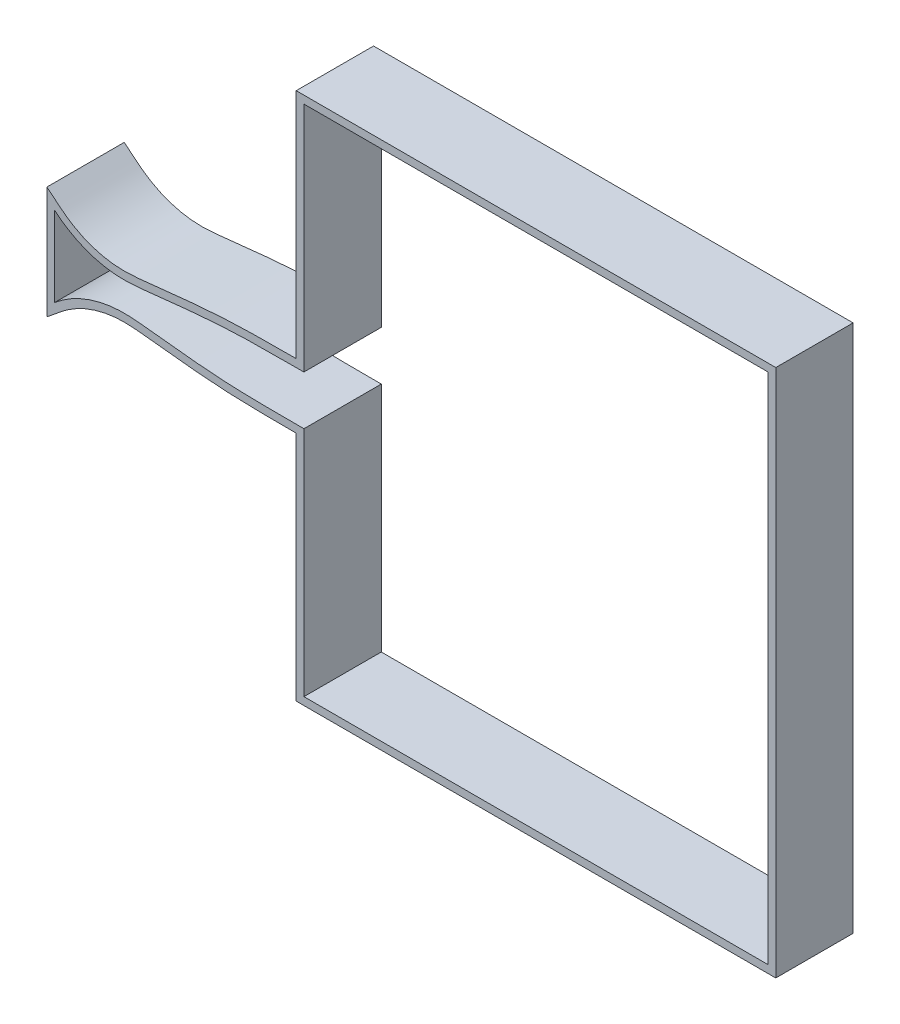
SolidWorks part; units mm, degrees
ref_plane "Front Plane"
ref_plane "Top Plane" through (0, 0, 0) normal (0, 1, 0) x (1, 0, 0)
ref_plane "Right Plane" through (0, 0, 0) normal (1, 0, 0) x (0, 0, -1)
curve "Curve1"
  spline degree 3 poles (-8.9943, 5.1625, 0) (-8.9922, 5.1608, 0) (-8.9859, 5.1556, 0) (-8.9711, 5.1434, 0) (-8.9416, 5.1188, 0) (-8.8898, 5.0757, 0) (-8.8197, 5.0179, 0) (-8.7395, 4.9527, 0) (-8.6589, 4.888, 0) (-8.5778, 4.824, 0) (-8.4963, 4.7605, 0) (-8.4142, 4.6976, 0) (-8.3317, 4.6353, 0) (-8.2488, 4.5736, 0) (-8.1654, 4.5124, 0) (-8.0816, 4.452, 0) (-7.9974, 4.3921, 0) (-7.9126, 4.3328, 0) (-7.8275, 4.2742, 0) (-7.742, 4.2163, 0) (-7.656, 4.1589, 0) (-7.5696, 4.1023, 0) (-7.4828, 4.0462, 0) (-7.3957, 3.9908, 0) (-7.3081, 3.9361, 0) (-7.2201, 3.882, 0) (-7.1317, 3.8286, 0) (-7.0429, 3.7759, 0) (-6.9538, 3.7238, 0) (-6.8643, 3.6723, 0) (-6.7744, 3.6216, 0) (-6.6841, 3.5715, 0) (-6.5935, 3.5221, 0) (-6.5025, 3.4734, 0) (-6.4112, 3.4253, 0) (-6.3195, 3.378, 0) (-6.2275, 3.3313, 0) (-6.1352, 3.2854, 0) (-6.0425, 3.24, 0) (-5.9495, 3.1954, 0) (-5.8562, 3.1515, 0) (-5.7625, 3.1084, 0) (-5.6686, 3.0658, 0) (-5.5744, 3.024, 0) (-5.4798, 2.9829, 0) (-5.385, 2.9425, 0) (-5.2898, 2.9028, 0) (-5.1944, 2.8639, 0) (-5.0987, 2.8256, 0) (-5.0028, 2.7881, 0) (-4.9065, 2.7512, 0) (-4.81, 2.7151, 0) (-4.7133, 2.6797, 0) (-4.6162, 2.6451, 0) (-4.519, 2.6111, 0) (-4.4215, 2.5779, 0) (-4.3237, 2.5454, 0) (-4.2258, 2.5137, 0) (-4.1276, 2.4826, 0) (-4.0292, 2.4524, 0) (-3.9306, 2.4227, 0) (-3.8317, 2.394, 0) (-3.7327, 2.3659, 0) (-3.6334, 2.3385, 0) (-3.534, 2.3119, 0) (-3.4344, 2.2861, 0) (-3.3346, 2.2609, 0) (-3.2346, 2.2365, 0) (-3.1344, 2.2129, 0) (-3.0341, 2.19, 0) (-2.9336, 2.1679, 0) (-2.833, 2.1465, 0) (-2.7322, 2.1258, 0) (-2.6313, 2.106, 0) (-2.5302, 2.0868, 0) (-2.4291, 2.0684, 0) (-2.3277, 2.0508, 0) (-2.2263, 2.0339, 0) (-2.1247, 2.0178, 0) (-2.0231, 2.0024, 0) (-1.9213, 1.9878, 0) (-1.8194, 1.974, 0) (-1.7175, 1.9609, 0) (-1.6154, 1.9486, 0) (-1.5133, 1.937, 0) (-1.411, 1.9262, 0) (-1.3088, 1.9161, 0) (-1.2064, 1.9068, 0) (-1.104, 1.8983, 0) (-1.0015, 1.8906, 0) (-0.899, 1.8836, 0) (-0.7965, 1.8773, 0) (-0.6939, 1.8719, 0) (-0.5913, 1.8672, 0) (-0.4886, 1.8632, 0) (-0.3859, 1.8601, 0) (-0.2832, 1.8576, 0) (-0.1805, 1.856, 0) (-0.0778, 1.8551, 0) (0.0249, 1.8549, 0) (0.1276, 1.8557, 0) (0.2302, 1.8571, 0) (0.3329, 1.8592, 0) (0.4355, 1.8621, 0) (0.5381, 1.8656, 0) (0.6407, 1.87, 0) (0.7433, 1.8748, 0) (0.8458, 1.8804, 0) (0.9483, 1.8864, 0) (1.0508, 1.893, 0) (1.1532, 1.9, 0) (1.2556, 1.9073, 0) (1.358, 1.9151, 0) (1.4604, 1.9232, 0) (1.5627, 1.9316, 0) (1.6651, 1.9402, 0) (1.7673, 1.9492, 0) (1.8696, 1.9583, 0) (1.9719, 1.9677, 0) (2.0742, 1.9772, 0) (2.1764, 1.9869, 0) (2.2786, 1.9969, 0) (2.3808, 2.0068, 0) (2.483, 2.017, 0) (2.5852, 2.0272, 0) (2.6874, 2.0375, 0) (2.7896, 2.048, 0) (2.8918, 2.0585, 0) (2.9939, 2.0691, 0) (3.0961, 2.0797, 0) (3.1982, 2.0904, 0) (3.3004, 2.1012, 0) (3.4025, 2.112, 0) (3.5047, 2.1228, 0) (3.6068, 2.1336, 0) (3.709, 2.1445, 0) (3.8111, 2.1554, 0) (3.9132, 2.1663, 0) (4.0154, 2.1772, 0) (4.1175, 2.1882, 0) (4.2196, 2.1991, 0) (4.3218, 2.21, 0) (4.4239, 2.221, 0) (4.526, 2.2319, 0) (4.6282, 2.2428, 0) (4.7303, 2.2538, 0) (4.8324, 2.2647, 0) (4.9346, 2.2757, 0) (5.0367, 2.2866, 0) (5.1388, 2.2976, 0) (5.241, 2.3085, 0) (5.3431, 2.3195, 0) (5.4453, 2.3304, 0) (5.5474, 2.3414, 0) (5.6495, 2.3523, 0) (5.7517, 2.3633, 0) (5.8538, 2.3742, 0) (5.9559, 2.3852, 0) (6.0581, 2.3962, 0) (6.1602, 2.4071, 0) (6.2623, 2.4181, 0) (6.3645, 2.4291, 0) (6.4666, 2.4401, 0) (6.5687, 2.451, 0) (6.6709, 2.462, 0) (6.773, 2.4729, 0) (6.8752, 2.4838, 0) (6.9773, 2.4947, 0) (7.0795, 2.5056, 0) (7.1816, 2.5165, 0) (7.2837, 2.5273, 0) (7.3859, 2.5382, 0) (7.4881, 2.5489, 0) (7.5902, 2.5596, 0) (7.6924, 2.5704, 0) (7.7946, 2.581, 0) (7.8967, 2.5916, 0) (7.9989, 2.6021, 0) (8.1011, 2.6126, 0) (8.2033, 2.623, 0) (8.3055, 2.6334, 0) (8.4077, 2.6436, 0) (8.5099, 2.6539, 0) (8.6122, 2.664, 0) (8.7144, 2.6741, 0) (8.8166, 2.684, 0) (8.9189, 2.6939, 0) (9.0211, 2.7037, 0) (9.1234, 2.7134, 0) (9.2257, 2.723, 0) (9.3279, 2.7325, 0) (9.4302, 2.742, 0) (9.5325, 2.7513, 0) (9.6348, 2.7605, 0) (9.7371, 2.7697, 0) (9.8395, 2.7786, 0) (9.9418, 2.7876, 0) (10.0442, 2.7963, 0) (10.1465, 2.8051, 0) (10.2489, 2.8136, 0) (10.3512, 2.8221, 0) (10.4536, 2.8304, 0) (10.556, 2.8387, 0) (10.6584, 2.8468, 0) (10.7608, 2.8549, 0) (10.8632, 2.8627, 0) (10.9657, 2.8705, 0) (11.0681, 2.8782, 0) (11.1705, 2.8857, 0) (11.273, 2.8932, 0) (11.3754, 2.9005, 0) (11.4779, 2.9078, 0) (11.5804, 2.9148, 0) (11.6828, 2.9218, 0) (11.7853, 2.9287, 0) (11.8878, 2.9355, 0) (11.9903, 2.942, 0) (12.0928, 2.9486, 0) (12.1953, 2.9549, 0) (12.2979, 2.9613, 0) (12.4004, 2.9675, 0) (12.5029, 2.9735, 0) (12.6055, 2.9795, 0) (12.708, 2.9853, 0) (12.8106, 2.9911, 0) (12.9131, 2.9967, 0) (13.0157, 3.0022, 0) (13.1183, 3.0076, 0) (13.2208, 3.0129, 0) (13.3234, 3.0182, 0) (13.426, 3.0232, 0) (13.5286, 3.0282, 0) (13.6312, 3.0331, 0) (13.7338, 3.0378, 0) (13.8364, 3.0425, 0) (13.939, 3.0471, 0) (14.0416, 3.0515, 0) (14.1442, 3.0559, 0) (14.2468, 3.0601, 0) (14.3495, 3.0642, 0) (14.4521, 3.0683, 0) (14.5547, 3.0722, 0) (14.6574, 3.0761, 0) (14.76, 3.0798, 0) (14.8626, 3.0835, 0) (14.9653, 3.087, 0) (15.0679, 3.0904, 0) (15.1706, 3.0938, 0) (15.2732, 3.097, 0) (15.3759, 3.1002, 0) (15.4786, 3.1032, 0) (15.5812, 3.1062, 0) (15.6839, 3.109, 0) (15.7866, 3.1118, 0) (15.8892, 3.1146, 0) (15.9919, 3.1171, 0) (16.0946, 3.1197, 0) (16.1972, 3.1221, 0) (16.2999, 3.1244, 0) (16.4026, 3.1267, 0) (16.5053, 3.1289, 0) (16.608, 3.131, 0) (16.7106, 3.133, 0) (16.8133, 3.1349, 0) (16.916, 3.1368, 0) (17.0187, 3.1386, 0) (17.1214, 3.1403, 0) (17.2241, 3.142, 0) (17.3268, 3.1436, 0) (17.4295, 3.1451, 0) (17.5321, 3.1465, 0) (17.6348, 3.1479, 0) (17.7375, 3.1492, 0) (17.8402, 3.1505, 0) (17.9429, 3.1517, 0) (18.0456, 3.1529, 0) (18.1483, 3.154, 0) (18.251, 3.1551, 0) (18.3537, 3.156, 0) (18.4564, 3.157, 0) (18.5591, 3.1579, 0) (18.6618, 3.1587, 0) (18.7645, 3.1596, 0) (18.8672, 3.1604, 0) (18.9699, 3.161, 0) (19.0726, 3.1617, 0) (19.1752, 3.1625, 0) (19.2779, 3.1631, 0) (19.3806, 3.1636, 0) (19.4833, 3.1642, 0) (19.586, 3.1647, 0) (19.6887, 3.1652, 0) (19.7914, 3.1657, 0) (19.8941, 3.1662, 0) (19.9968, 3.1666, 0) (20.0995, 3.167, 0) (20.2022, 3.1674, 0) (20.3049, 3.1678, 0) (20.4076, 3.1682, 0) (20.5103, 3.1685, 0) (20.613, 3.1688, 0) (20.7157, 3.1691, 0) (20.8184, 3.1694, 0) (20.9211, 3.1697, 0) (21.0238, 3.17, 0) (21.1265, 3.1703, 0) (21.2292, 3.1705, 0) (21.3319, 3.1708, 0) (21.4346, 3.1711, 0) (21.5373, 3.1713, 0) (21.64, 3.1715, 0) (21.7427, 3.1718, 0) (21.8454, 3.172, 0) (21.9481, 3.1723, 0) (22.0508, 3.1724, 0) (22.1535, 3.1727, 0) (22.2562, 3.1729, 0) (22.3589, 3.1732, 0) (22.4616, 3.1733, 0) (22.5643, 3.1736, 0) (22.667, 3.1738, 0) (22.7697, 3.174, 0) (22.8724, 3.1743, 0) (22.9751, 3.1745, 0) (23.0778, 3.1747, 0) (23.1659, 3.1748, 0) (23.2198, 3.175, 0) (23.2395, 3.175, 0) knots 0 0 0 0 0.000245 0.000742 0.001737 0.003732 0.006854 0.009976 0.013101 0.016226 0.019351 0.022475 0.025601 0.028726 0.031851 0.034975 0.0381 0.041225 0.044348 0.047472 0.050596 0.053718 0.056842 0.059964 0.063086 0.066209 0.069331 0.072452 0.075573 0.078694 0.081814 0.084935 0.088054 0.091174 0.094294 0.097413 0.100531 0.10365 0.106768 0.109886 0.113003 0.116121 0.119237 0.122355 0.125471 0.128587 0.131704 0.134819 0.137934 0.141051 0.144164 0.147279 0.150394 0.153508 0.156622 0.159735 0.16285 0.165963 0.169076 0.172189 0.175301 0.178413 0.181525 0.184637 0.187749 0.19086 0.193971 0.197082 0.200193 0.203303 0.206413 0.209524 0.212633 0.215743 0.218852 0.221961 0.22507 0.228179 0.231287 0.234395 0.237504 0.240612 0.243719 0.246826 0.249933 0.253041 0.256148 0.259254 0.262361 0.265468 0.268574 0.27168 0.274785 0.277891 0.280996 0.284101 0.287206 0.290311 0.293417 0.296522 0.299625 0.302729 0.305833 0.308937 0.312041 0.315145 0.318249 0.321352 0.324457 0.32756 0.330664 0.333768 0.336872 0.339976 0.343081 0.346185 0.349289 0.352394 0.355499 0.358603 0.361708 0.364812 0.367916 0.371021 0.374126 0.377231 0.380336 0.38344 0.386545 0.38965 0.392756 0.39586 0.398966 0.40207 0.405176 0.40828 0.411386 0.414491 0.417596 0.420702 0.423806 0.426911 0.430017 0.433122 0.436227 0.439332 0.442438 0.445542 0.448647 0.451753 0.454858 0.457963 0.461069 0.464174 0.467279 0.470384 0.47349 0.476595 0.4797 0.482806 0.485911 0.489015 0.492122 0.495226 0.498331 0.501437 0.504542 0.507648 0.510753 0.513858 0.516963 0.520069 0.523174 0.526279 0.529385 0.53249 0.535596 0.538701 0.541807 0.544911 0.548016 0.551122 0.554228 0.557333 0.560438 0.563544 0.566649 0.569754 0.572859 0.575965 0.57907 0.582175 0.58528 0.588386 0.591491 0.594596 0.597702 0.600807 0.603913 0.607017 0.610122 0.613228 0.616333 0.619438 0.622544 0.625649 0.628753 0.631859 0.634963 0.638069 0.641174 0.64428 0.647384 0.65049 0.653595 0.6567 0.659805 0.662909 0.666015 0.66912 0.672224 0.67533 0.678435 0.68154 0.684644 0.68775 0.690855 0.69396 0.697065 0.70017 0.703274 0.706379 0.709484 0.71259 0.715694 0.718799 0.721904 0.725009 0.728113 0.731218 0.734324 0.737428 0.740533 0.743638 0.746743 0.749848 0.752952 0.756057 0.759161 0.762266 0.765371 0.768477 0.771581 0.774686 0.77779 0.780896 0.784 0.787104 0.790209 0.793313 0.796419 0.799524 0.802628 0.805733 0.808838 0.811941 0.815046 0.818151 0.821256 0.824361 0.827465 0.83057 0.833674 0.836779 0.839884 0.842989 0.846093 0.849198 0.852303 0.855406 0.858511 0.861615 0.86472 0.867825 0.870929 0.874034 0.877138 0.880243 0.883347 0.886452 0.889557 0.892661 0.895766 0.89887 0.901975 0.905079 0.908184 0.911289 0.914393 0.917498 0.920602 0.923707 0.926811 0.929916 0.93302 0.936125 0.939229 0.942334 0.945438 0.948543 0.951648 0.954752 0.957857 0.960961 0.964066 0.96717 0.970275 0.973379 0.976484 0.979588 0.982693 0.985797 0.988902 0.992006 0.995111 0.998216 1 1 1 1
sketch "Sketch1" plane through (0, 0, 0) normal (0, 0, 1) x (1, 0, 0)
  line L0 (0, 0) -> (27.8721, 0) construction
  line L1 (-8.9943, 5.1625) -> (-8.9943, -5.1625)
  line L2 (23.2395, 3.175) -> (23.2395, 33.175)
  line L3 (23.2395, 33.175) -> (83.2395, 33.175)
  line L4 (83.2395, 33.175) -> (83.2395, -33.175)
  line L5 (83.2395, -33.175) -> (23.2395, -33.175)
  line L6 (23.2395, -33.175) -> (23.2395, -3.175)
  line L7 (22.2395, 4.1729) -> (22.2395, 34.175)
  line L8 (22.2395, 34.175) -> (84.2395, 34.175)
  line L9 (84.2395, 34.175) -> (84.2395, -34.175)
  line L10 (84.2395, -34.175) -> (22.2395, -34.175)
  line L11 (22.2395, -34.175) -> (22.2395, -4.1729)
  line L12 (-9.9943, 7.268) -> (-9.9943, -7.268)
  spline S0 degree 3 poles (1890.1169, 2325.3091) (-14.6496, 4.303) (-10.4572, 6.3786) (-8.9711, 5.1434) (-8.9416, 5.1188) (-8.8898, 5.0757) (-8.8197, 5.0179) (-8.7395, 4.9527) (-8.6589, 4.888) (-8.5778, 4.824) (-8.4963, 4.7605) (-8.4142, 4.6976) (-8.3317, 4.6353) (-8.2488, 4.5736) (-8.1654, 4.5124) (-8.0816, 4.452) (-7.9974, 4.3921) (-7.9126, 4.3328) (-7.8275, 4.2742) (-7.742, 4.2163) (-7.656, 4.1589) (-7.5696, 4.1023) (-7.4828, 4.0462) (-7.3666, 3.9724) (-7.2495, 3.8998) (-7.1022, 3.8108) (-6.9836, 3.7409) (-6.8643, 3.6723) (-6.7744, 3.6216) (-6.6841, 3.5715) (-6.5935, 3.5221) (-6.5025, 3.4734) (-6.3808, 3.4093) (-6.2583, 3.3466) (-6.1352, 3.2854) (-6.0425, 3.24) (-5.9495, 3.1954) (-5.8562, 3.1515) (-5.7625, 3.1084) (-5.6373, 3.0516) (-5.5114, 2.9964) (-5.385, 2.9425) (-5.2898, 2.9028) (-5.1944, 2.8639) (-5.0987, 2.8256) (-5.0028, 2.7881) (-4.9065, 2.7512) (-4.81, 2.7151) (-4.7133, 2.6797) (-4.6162, 2.6451) (-4.519, 2.6111) (-4.4215, 2.5779) (-4.3237, 2.5454) (-4.2258, 2.5137) (-4.1276, 2.4826) (-4.0292, 2.4524) (-3.9306, 2.4227) (-3.8317, 2.394) (-3.7327, 2.3659) (-3.6334, 2.3385) (-3.534, 2.3119) (-3.4344, 2.2861) (-3.3346, 2.2609) (-3.2346, 2.2365) (-3.1344, 2.2129) (-3.0341, 2.19) (-2.9336, 2.1679) (-2.833, 2.1465) (-2.7322, 2.1258) (-2.6313, 2.106) (-2.5302, 2.0868) (-2.4291, 2.0684) (-2.3277, 2.0508) (-2.2263, 2.0339) (-2.1247, 2.0178) (-2.0231, 2.0024) (-1.9213, 1.9878) (-1.8194, 1.974) (-1.7175, 1.9609) (-1.6154, 1.9486) (-1.5133, 1.937) (-1.411, 1.9262) (-1.3088, 1.9161) (-1.2064, 1.9068) (-1.104, 1.8983) (-1.0015, 1.8906) (-0.899, 1.8836) (-0.7965, 1.8773) (-0.6939, 1.8719) (-0.5913, 1.8672) (-0.4886, 1.8632) (-0.3859, 1.8601) (-0.2832, 1.8576) (-0.1805, 1.856) (-0.0778, 1.8551) (0.0249, 1.8549) (0.1276, 1.8557) (0.2302, 1.8571) (0.3329, 1.8592) (0.4355, 1.8621) (0.5381, 1.8656) (0.6407, 1.87) (0.7433, 1.8748) (0.8458, 1.8804) (0.9483, 1.8864) (1.0508, 1.893) (1.1532, 1.9) (1.2556, 1.9073) (1.358, 1.9151) (1.4604, 1.9232) (1.5627, 1.9316) (1.6651, 1.9402) (1.7673, 1.9492) (1.8696, 1.9583) (1.9719, 1.9677) (2.0742, 1.9772) (2.1764, 1.9869) (2.2786, 1.9969) (2.3808, 2.0068) (2.483, 2.017) (2.5852, 2.0272) (2.7215, 2.041) (2.8577, 2.055) (2.9939, 2.0691) (3.0961, 2.0797) (3.1982, 2.0904) (3.3004, 2.1012) (3.4366, 2.1156) (3.5728, 2.13) (3.709, 2.1445) (3.8111, 2.1554) (3.9132, 2.1663) (4.0154, 2.1772) (4.1175, 2.1882) (4.2196, 2.1991) (4.3218, 2.21) (4.4579, 2.2247) (4.5941, 2.2392) (4.7303, 2.2538) (4.8324, 2.2647) (4.9346, 2.2757) (5.0367, 2.2866) (5.1388, 2.2976) (5.241, 2.3085) (5.3431, 2.3195) (5.4453, 2.3304) (5.5474, 2.3414) (5.6495, 2.3523) (5.7517, 2.3633) (5.8538, 2.3742) (5.99, 2.3889) (6.1262, 2.4035) (6.2623, 2.4181) (6.3645, 2.4291) (6.4666, 2.4401) (6.5687, 2.451) (6.6709, 2.462) (6.773, 2.4729) (6.8752, 2.4838) (6.9773, 2.4947) (7.0795, 2.5056) (7.1816, 2.5165) (7.2837, 2.5273) (7.3859, 2.5382) (7.4881, 2.5489) (7.5902, 2.5596) (7.6924, 2.5704) (7.7946, 2.581) (7.8967, 2.5916) (7.9989, 2.6021) (8.1011, 2.6126) (8.2033, 2.623) (8.3055, 2.6334) (8.4077, 2.6436) (8.5099, 2.6539) (8.6122, 2.664) (8.7144, 2.6741) (8.8166, 2.684) (8.9189, 2.6939) (9.0211, 2.7037) (9.1575, 2.7166) (9.2938, 2.7294) (9.4302, 2.742) (9.5325, 2.7513) (9.6348, 2.7605) (9.7371, 2.7697) (9.8395, 2.7786) (9.9418, 2.7876) (10.0442, 2.7963) (10.1465, 2.8051) (10.2489, 2.8136) (10.3512, 2.8221) (10.4536, 2.8304) (10.556, 2.8387) (10.6584, 2.8468) (10.7608, 2.8549) (10.8974, 2.8654) (11.0339, 2.8757) (11.2047, 2.8882) (11.3413, 2.8981) (11.4779, 2.9078) (11.5804, 2.9148) (11.6828, 2.9218) (11.7853, 2.9287) (11.8878, 2.9355) (11.9903, 2.942) (12.0928, 2.9486) (12.1953, 2.9549) (12.2979, 2.9613) (12.4004, 2.9675) (12.5029, 2.9735) (12.6055, 2.9795) (12.708, 2.9853) (12.8106, 2.9911) (12.9131, 2.9967) (13.0157, 3.0022) (13.1183, 3.0076) (13.2208, 3.0129) (13.3234, 3.0182) (13.426, 3.0232) (13.5286, 3.0282) (13.6312, 3.0331) (13.7338, 3.0378) (13.8364, 3.0425) (13.939, 3.0471) (14.0416, 3.0515) (14.1442, 3.0559) (14.2468, 3.0601) (14.3495, 3.0642) (14.4521, 3.0683) (14.5547, 3.0722) (14.6574, 3.0761) (14.76, 3.0798) (14.8626, 3.0835) (14.9653, 3.087) (15.0679, 3.0904) (15.1706, 3.0938) (15.2732, 3.097) (15.3759, 3.1002) (15.5128, 3.1042) (15.6497, 3.1081) (15.7866, 3.1118) (15.8892, 3.1146) (15.9919, 3.1171) (16.0946, 3.1197) (16.1972, 3.1221) (16.3684, 3.126) (16.5395, 3.1296) (16.7106, 3.133) (16.8133, 3.1349) (16.916, 3.1368) (17.0187, 3.1386) (17.1214, 3.1403) (17.2241, 3.142) (17.3268, 3.1436) (17.4295, 3.1451) (17.5321, 3.1465) (17.6348, 3.1479) (17.7375, 3.1492) (17.8402, 3.1505) (17.9429, 3.1517) (18.0456, 3.1529) (18.1483, 3.154) (18.251, 3.1551) (18.3537, 3.156) (18.4906, 3.1573) (18.6275, 3.1585) (18.7645, 3.1596) (18.8672, 3.1604) (18.9699, 3.161) (19.0726, 3.1617) (19.2095, 3.1627) (19.3464, 3.1634) (19.4833, 3.1642) (19.586, 3.1647) (19.6887, 3.1652) (19.7914, 3.1657) (19.8941, 3.1662) (19.9968, 3.1666) (20.0995, 3.167) (20.2022, 3.1674) (20.3049, 3.1678) (20.4076, 3.1682) (20.5103, 3.1685) (20.613, 3.1688) (20.7157, 3.1691) (20.8184, 3.1694) (20.9211, 3.1697) (21.0238, 3.17) (21.1265, 3.1703) (21.2292, 3.1705) (21.3319, 3.1708) (21.4346, 3.1711) (21.5373, 3.1713) (21.64, 3.1715) (21.7427, 3.1718) (21.8454, 3.172) (21.9481, 3.1723) (22.0508, 3.1724) (22.1535, 3.1727) (22.2562, 3.1729) (22.3589, 3.1732) (22.4616, 3.1733) (22.5985, 3.1737) (22.7354, 3.1739) (22.8724, 3.1743) (22.9751, 3.1745) (23.0778, 3.1747) (51.5319, 3.2305) (79.9475, 5.3737) (114.5254, -2994.6334) knots -0.173504 -0.173504 -0.173504 -0.173504 0.000245 0.000742 0.001737 0.003732 0.006854 0.009976 0.013101 0.016226 0.019351 0.022475 0.025601 0.028726 0.031851 0.034975 0.0381 0.041225 0.044348 0.047472 0.050596 0.053718 0.056842 0.059964 0.066209 0.069331 0.075573 0.078694 0.081814 0.084935 0.088054 0.091174 0.094294 0.100531 0.10365 0.106768 0.109886 0.113003 0.116121 0.119237 0.125471 0.128587 0.131704 0.134819 0.137934 0.141051 0.144164 0.147279 0.150394 0.153508 0.156622 0.159735 0.16285 0.165963 0.169076 0.172189 0.175301 0.178413 0.181525 0.184637 0.187749 0.19086 0.193971 0.197082 0.200193 0.203303 0.206413 0.209524 0.212633 0.215743 0.218852 0.221961 0.22507 0.228179 0.231287 0.234395 0.237504 0.240612 0.243719 0.246826 0.249933 0.253041 0.256148 0.259254 0.262361 0.265468 0.268574 0.27168 0.274785 0.277891 0.280996 0.284101 0.287206 0.290311 0.293417 0.296522 0.299625 0.302729 0.305833 0.308937 0.312041 0.315145 0.318249 0.321352 0.324457 0.32756 0.330664 0.333768 0.336872 0.339976 0.343081 0.346185 0.349289 0.352394 0.355499 0.358603 0.361708 0.364812 0.367916 0.371021 0.374126 0.377231 0.38344 0.386545 0.38965 0.392756 0.39586 0.398966 0.405176 0.40828 0.411386 0.414491 0.417596 0.420702 0.423806 0.426911 0.430017 0.436227 0.439332 0.442438 0.445542 0.448647 0.451753 0.454858 0.457963 0.461069 0.464174 0.467279 0.470384 0.47349 0.476595 0.482806 0.485911 0.489015 0.492122 0.495226 0.498331 0.501437 0.504542 0.507648 0.510753 0.513858 0.516963 0.520069 0.523174 0.526279 0.529385 0.53249 0.535596 0.538701 0.541807 0.544911 0.548016 0.551122 0.554228 0.557333 0.560438 0.563544 0.566649 0.569754 0.572859 0.57907 0.582175 0.58528 0.588386 0.591491 0.594596 0.597702 0.600807 0.603913 0.607017 0.610122 0.613228 0.616333 0.619438 0.622544 0.625649 0.631859 0.634963 0.641174 0.64428 0.647384 0.65049 0.653595 0.6567 0.659805 0.662909 0.666015 0.66912 0.672224 0.67533 0.678435 0.68154 0.684644 0.68775 0.690855 0.69396 0.697065 0.70017 0.703274 0.706379 0.709484 0.71259 0.715694 0.718799 0.721904 0.725009 0.728113 0.731218 0.734324 0.737428 0.740533 0.743638 0.746743 0.749848 0.752952 0.756057 0.759161 0.762266 0.765371 0.771581 0.774686 0.77779 0.780896 0.784 0.787104 0.790209 0.799524 0.802628 0.805733 0.808838 0.811941 0.815046 0.818151 0.821256 0.824361 0.827465 0.83057 0.833674 0.836779 0.839884 0.842989 0.846093 0.849198 0.852303 0.855406 0.861615 0.86472 0.867825 0.870929 0.874034 0.877138 0.883347 0.886452 0.889557 0.892661 0.895766 0.89887 0.901975 0.905079 0.908184 0.911289 0.914393 0.917498 0.920602 0.923707 0.926811 0.929916 0.93302 0.936125 0.939229 0.942334 0.945438 0.948543 0.951648 0.954752 0.957857 0.960961 0.964066 0.96717 0.970275 0.973379 0.976484 0.979588 0.985797 0.988902 0.992006 0.995111 0.998216 3.572497 3.572497 3.572497 3.572497 only from (-8.9943, 5.1625) to (23.2395, 3.175) construction
  spline S1 degree 3 poles (-8.9943, 5.1625) (-8.9922, 5.1608) (-8.9859, 5.1556) (-8.9711, 5.1434) (-8.9416, 5.1188) (-8.8898, 5.0757) (-8.8197, 5.0179) (-8.7395, 4.9527) (-8.6589, 4.888) (-8.5778, 4.824) (-8.4963, 4.7605) (-8.4142, 4.6976) (-8.3317, 4.6353) (-8.2488, 4.5736) (-8.1654, 4.5124) (-8.0816, 4.452) (-7.9974, 4.3921) (-7.9126, 4.3328) (-7.8275, 4.2742) (-7.742, 4.2163) (-7.656, 4.1589) (-7.5696, 4.1023) (-7.4828, 4.0462) (-7.3666, 3.9724) (-7.2495, 3.8998) (-7.1022, 3.8108) (-6.9836, 3.7409) (-6.8643, 3.6723) (-6.7744, 3.6216) (-6.6841, 3.5715) (-6.5935, 3.5221) (-6.5025, 3.4734) (-6.3808, 3.4093) (-6.2583, 3.3466) (-6.1352, 3.2854) (-6.0425, 3.24) (-5.9495, 3.1954) (-5.8562, 3.1515) (-5.7625, 3.1084) (-5.6373, 3.0516) (-5.5114, 2.9964) (-5.385, 2.9425) (-5.2898, 2.9028) (-5.1944, 2.8639) (-5.0987, 2.8256) (-5.0028, 2.7881) (-4.9065, 2.7512) (-4.81, 2.7151) (-4.7133, 2.6797) (-4.6162, 2.6451) (-4.519, 2.6111) (-4.4215, 2.5779) (-4.3237, 2.5454) (-4.2258, 2.5137) (-4.1276, 2.4826) (-4.0292, 2.4524) (-3.9306, 2.4227) (-3.8317, 2.394) (-3.7327, 2.3659) (-3.6334, 2.3385) (-3.534, 2.3119) (-3.4344, 2.2861) (-3.3346, 2.2609) (-3.2346, 2.2365) (-3.1344, 2.2129) (-3.0341, 2.19) (-2.9336, 2.1679) (-2.833, 2.1465) (-2.7322, 2.1258) (-2.6313, 2.106) (-2.5302, 2.0868) (-2.4291, 2.0684) (-2.3277, 2.0508) (-2.2263, 2.0339) (-2.1247, 2.0178) (-2.0231, 2.0024) (-1.9213, 1.9878) (-1.8194, 1.974) (-1.7175, 1.9609) (-1.6154, 1.9486) (-1.5133, 1.937) (-1.411, 1.9262) (-1.3088, 1.9161) (-1.2064, 1.9068) (-1.104, 1.8983) (-1.0015, 1.8906) (-0.899, 1.8836) (-0.7965, 1.8773) (-0.6939, 1.8719) (-0.5913, 1.8672) (-0.4886, 1.8632) (-0.3859, 1.8601) (-0.2832, 1.8576) (-0.1805, 1.856) (-0.0778, 1.8551) (0.0249, 1.8549) (0.1276, 1.8557) (0.2302, 1.8571) (0.3329, 1.8592) (0.4355, 1.8621) (0.5381, 1.8656) (0.6407, 1.87) (0.7433, 1.8748) (0.8458, 1.8804) (0.9483, 1.8864) (1.0508, 1.893) (1.1532, 1.9) (1.2556, 1.9073) (1.358, 1.9151) (1.4604, 1.9232) (1.5627, 1.9316) (1.6651, 1.9402) (1.7673, 1.9492) (1.8696, 1.9583) (1.9719, 1.9677) (2.0742, 1.9772) (2.1764, 1.9869) (2.2786, 1.9969) (2.3808, 2.0068) (2.483, 2.017) (2.5852, 2.0272) (2.7215, 2.041) (2.8577, 2.055) (2.9939, 2.0691) (3.0961, 2.0797) (3.1982, 2.0904) (3.3004, 2.1012) (3.4366, 2.1156) (3.5728, 2.13) (3.709, 2.1445) (3.8111, 2.1554) (3.9132, 2.1663) (4.0154, 2.1772) (4.1175, 2.1882) (4.2196, 2.1991) (4.3218, 2.21) (4.4579, 2.2247) (4.5941, 2.2392) (4.7303, 2.2538) (4.8324, 2.2647) (4.9346, 2.2757) (5.0367, 2.2866) (5.1388, 2.2976) (5.241, 2.3085) (5.3431, 2.3195) (5.4453, 2.3304) (5.5474, 2.3414) (5.6495, 2.3523) (5.7517, 2.3633) (5.8538, 2.3742) (5.99, 2.3889) (6.1262, 2.4035) (6.2623, 2.4181) (6.3645, 2.4291) (6.4666, 2.4401) (6.5687, 2.451) (6.6709, 2.462) (6.773, 2.4729) (6.8752, 2.4838) (6.9773, 2.4947) (7.0795, 2.5056) (7.1816, 2.5165) (7.2837, 2.5273) (7.3859, 2.5382) (7.4881, 2.5489) (7.5902, 2.5596) (7.6924, 2.5704) (7.7946, 2.581) (7.8967, 2.5916) (7.9989, 2.6021) (8.1011, 2.6126) (8.2033, 2.623) (8.3055, 2.6334) (8.4077, 2.6436) (8.5099, 2.6539) (8.6122, 2.664) (8.7144, 2.6741) (8.8166, 2.684) (8.9189, 2.6939) (9.0211, 2.7037) (9.1575, 2.7166) (9.2938, 2.7294) (9.4302, 2.742) (9.5325, 2.7513) (9.6348, 2.7605) (9.7371, 2.7697) (9.8395, 2.7786) (9.9418, 2.7876) (10.0442, 2.7963) (10.1465, 2.8051) (10.2489, 2.8136) (10.3512, 2.8221) (10.4536, 2.8304) (10.556, 2.8387) (10.6584, 2.8468) (10.7608, 2.8549) (10.8974, 2.8654) (11.0339, 2.8757) (11.2047, 2.8882) (11.3413, 2.8981) (11.4779, 2.9078) (11.5804, 2.9148) (11.6828, 2.9218) (11.7853, 2.9287) (11.8878, 2.9355) (11.9903, 2.942) (12.0928, 2.9486) (12.1953, 2.9549) (12.2979, 2.9613) (12.4004, 2.9675) (12.5029, 2.9735) (12.6055, 2.9795) (12.708, 2.9853) (12.8106, 2.9911) (12.9131, 2.9967) (13.0157, 3.0022) (13.1183, 3.0076) (13.2208, 3.0129) (13.3234, 3.0182) (13.426, 3.0232) (13.5286, 3.0282) (13.6312, 3.0331) (13.7338, 3.0378) (13.8364, 3.0425) (13.939, 3.0471) (14.0416, 3.0515) (14.1442, 3.0559) (14.2468, 3.0601) (14.3495, 3.0642) (14.4521, 3.0683) (14.5547, 3.0722) (14.6574, 3.0761) (14.76, 3.0798) (14.8626, 3.0835) (14.9653, 3.087) (15.0679, 3.0904) (15.1706, 3.0938) (15.2732, 3.097) (15.3759, 3.1002) (15.5128, 3.1042) (15.6497, 3.1081) (15.7866, 3.1118) (15.8892, 3.1146) (15.9919, 3.1171) (16.0946, 3.1197) (16.1972, 3.1221) (16.3684, 3.126) (16.5395, 3.1296) (16.7106, 3.133) (16.8133, 3.1349) (16.916, 3.1368) (17.0187, 3.1386) (17.1214, 3.1403) (17.2241, 3.142) (17.3268, 3.1436) (17.4295, 3.1451) (17.5321, 3.1465) (17.6348, 3.1479) (17.7375, 3.1492) (17.8402, 3.1505) (17.9429, 3.1517) (18.0456, 3.1529) (18.1483, 3.154) (18.251, 3.1551) (18.3537, 3.156) (18.4906, 3.1573) (18.6275, 3.1585) (18.7645, 3.1596) (18.8672, 3.1604) (18.9699, 3.161) (19.0726, 3.1617) (19.2095, 3.1627) (19.3464, 3.1634) (19.4833, 3.1642) (19.586, 3.1647) (19.6887, 3.1652) (19.7914, 3.1657) (19.8941, 3.1662) (19.9968, 3.1666) (20.0995, 3.167) (20.2022, 3.1674) (20.3049, 3.1678) (20.4076, 3.1682) (20.5103, 3.1685) (20.613, 3.1688) (20.7157, 3.1691) (20.8184, 3.1694) (20.9211, 3.1697) (21.0238, 3.17) (21.1265, 3.1703) (21.2292, 3.1705) (21.3319, 3.1708) (21.4346, 3.1711) (21.5373, 3.1713) (21.64, 3.1715) (21.7427, 3.1718) (21.8454, 3.172) (21.9481, 3.1723) (22.0508, 3.1724) (22.1535, 3.1727) (22.2562, 3.1729) (22.3589, 3.1732) (22.4616, 3.1733) (22.5985, 3.1737) (22.7354, 3.1739) (22.8724, 3.1743) (22.9751, 3.1745) (23.0778, 3.1747) (23.1659, 3.1748) (23.2198, 3.175) (23.2395, 3.175) knots 0 0 0 0 0.000245 0.000742 0.001737 0.003732 0.006854 0.009976 0.013101 0.016226 0.019351 0.022475 0.025601 0.028726 0.031851 0.034975 0.0381 0.041225 0.044348 0.047472 0.050596 0.053718 0.056842 0.059964 0.066209 0.069331 0.075573 0.078694 0.081814 0.084935 0.088054 0.091174 0.094294 0.100531 0.10365 0.106768 0.109886 0.113003 0.116121 0.119237 0.125471 0.128587 0.131704 0.134819 0.137934 0.141051 0.144164 0.147279 0.150394 0.153508 0.156622 0.159735 0.16285 0.165963 0.169076 0.172189 0.175301 0.178413 0.181525 0.184637 0.187749 0.19086 0.193971 0.197082 0.200193 0.203303 0.206413 0.209524 0.212633 0.215743 0.218852 0.221961 0.22507 0.228179 0.231287 0.234395 0.237504 0.240612 0.243719 0.246826 0.249933 0.253041 0.256148 0.259254 0.262361 0.265468 0.268574 0.27168 0.274785 0.277891 0.280996 0.284101 0.287206 0.290311 0.293417 0.296522 0.299625 0.302729 0.305833 0.308937 0.312041 0.315145 0.318249 0.321352 0.324457 0.32756 0.330664 0.333768 0.336872 0.339976 0.343081 0.346185 0.349289 0.352394 0.355499 0.358603 0.361708 0.364812 0.367916 0.371021 0.374126 0.377231 0.38344 0.386545 0.38965 0.392756 0.39586 0.398966 0.405176 0.40828 0.411386 0.414491 0.417596 0.420702 0.423806 0.426911 0.430017 0.436227 0.439332 0.442438 0.445542 0.448647 0.451753 0.454858 0.457963 0.461069 0.464174 0.467279 0.470384 0.47349 0.476595 0.482806 0.485911 0.489015 0.492122 0.495226 0.498331 0.501437 0.504542 0.507648 0.510753 0.513858 0.516963 0.520069 0.523174 0.526279 0.529385 0.53249 0.535596 0.538701 0.541807 0.544911 0.548016 0.551122 0.554228 0.557333 0.560438 0.563544 0.566649 0.569754 0.572859 0.57907 0.582175 0.58528 0.588386 0.591491 0.594596 0.597702 0.600807 0.603913 0.607017 0.610122 0.613228 0.616333 0.619438 0.622544 0.625649 0.631859 0.634963 0.641174 0.64428 0.647384 0.65049 0.653595 0.6567 0.659805 0.662909 0.666015 0.66912 0.672224 0.67533 0.678435 0.68154 0.684644 0.68775 0.690855 0.69396 0.697065 0.70017 0.703274 0.706379 0.709484 0.71259 0.715694 0.718799 0.721904 0.725009 0.728113 0.731218 0.734324 0.737428 0.740533 0.743638 0.746743 0.749848 0.752952 0.756057 0.759161 0.762266 0.765371 0.771581 0.774686 0.77779 0.780896 0.784 0.787104 0.790209 0.799524 0.802628 0.805733 0.808838 0.811941 0.815046 0.818151 0.821256 0.824361 0.827465 0.83057 0.833674 0.836779 0.839884 0.842989 0.846093 0.849198 0.852303 0.855406 0.861615 0.86472 0.867825 0.870929 0.874034 0.877138 0.883347 0.886452 0.889557 0.892661 0.895766 0.89887 0.901975 0.905079 0.908184 0.911289 0.914393 0.917498 0.920602 0.923707 0.926811 0.929916 0.93302 0.936125 0.939229 0.942334 0.945438 0.948543 0.951648 0.954752 0.957857 0.960961 0.964066 0.96717 0.970275 0.973379 0.976484 0.979588 0.985797 0.988902 0.992006 0.995111 0.998216 1 1 1 1
  spline S2 degree 3 poles (-8.9943, -5.1625) (-8.9922, -5.1608) (-8.9859, -5.1556) (-8.9711, -5.1434) (-8.9416, -5.1188) (-8.8898, -5.0757) (-8.8197, -5.0179) (-8.7395, -4.9527) (-8.6589, -4.888) (-8.5778, -4.824) (-8.4963, -4.7605) (-8.4142, -4.6976) (-8.3317, -4.6353) (-8.2488, -4.5736) (-8.1654, -4.5124) (-8.0816, -4.452) (-7.9974, -4.3921) (-7.9126, -4.3328) (-7.8275, -4.2742) (-7.742, -4.2163) (-7.656, -4.1589) (-7.5696, -4.1023) (-7.4828, -4.0462) (-7.3666, -3.9724) (-7.2495, -3.8998) (-7.1022, -3.8108) (-6.9836, -3.7409) (-6.8643, -3.6723) (-6.7744, -3.6216) (-6.6841, -3.5715) (-6.5935, -3.5221) (-6.5025, -3.4734) (-6.3808, -3.4093) (-6.2583, -3.3466) (-6.1352, -3.2854) (-6.0425, -3.24) (-5.9495, -3.1954) (-5.8562, -3.1515) (-5.7625, -3.1084) (-5.6373, -3.0516) (-5.5114, -2.9964) (-5.385, -2.9425) (-5.2898, -2.9028) (-5.1944, -2.8639) (-5.0987, -2.8256) (-5.0028, -2.7881) (-4.9065, -2.7512) (-4.81, -2.7151) (-4.7133, -2.6797) (-4.6162, -2.6451) (-4.519, -2.6111) (-4.4215, -2.5779) (-4.3237, -2.5454) (-4.2258, -2.5137) (-4.1276, -2.4826) (-4.0292, -2.4524) (-3.9306, -2.4227) (-3.8317, -2.394) (-3.7327, -2.3659) (-3.6334, -2.3385) (-3.534, -2.3119) (-3.4344, -2.2861) (-3.3346, -2.2609) (-3.2346, -2.2365) (-3.1344, -2.2129) (-3.0341, -2.19) (-2.9336, -2.1679) (-2.833, -2.1465) (-2.7322, -2.1258) (-2.6313, -2.106) (-2.5302, -2.0868) (-2.4291, -2.0684) (-2.3277, -2.0508) (-2.2263, -2.0339) (-2.1247, -2.0178) (-2.0231, -2.0024) (-1.9213, -1.9878) (-1.8194, -1.974) (-1.7175, -1.9609) (-1.6154, -1.9486) (-1.5133, -1.937) (-1.411, -1.9262) (-1.3088, -1.9161) (-1.2064, -1.9068) (-1.104, -1.8983) (-1.0015, -1.8906) (-0.899, -1.8836) (-0.7965, -1.8773) (-0.6939, -1.8719) (-0.5913, -1.8672) (-0.4886, -1.8632) (-0.3859, -1.8601) (-0.2832, -1.8576) (-0.1805, -1.856) (-0.0778, -1.8551) (0.0249, -1.8549) (0.1276, -1.8557) (0.2302, -1.8571) (0.3329, -1.8592) (0.4355, -1.8621) (0.5381, -1.8656) (0.6407, -1.87) (0.7433, -1.8748) (0.8458, -1.8804) (0.9483, -1.8864) (1.0508, -1.893) (1.1532, -1.9) (1.2556, -1.9073) (1.358, -1.9151) (1.4604, -1.9232) (1.5627, -1.9316) (1.6651, -1.9402) (1.7673, -1.9492) (1.8696, -1.9583) (1.9719, -1.9677) (2.0742, -1.9772) (2.1764, -1.9869) (2.2786, -1.9969) (2.3808, -2.0068) (2.483, -2.017) (2.5852, -2.0272) (2.7215, -2.041) (2.8577, -2.055) (2.9939, -2.0691) (3.0961, -2.0797) (3.1982, -2.0904) (3.3004, -2.1012) (3.4366, -2.1156) (3.5728, -2.13) (3.709, -2.1445) (3.8111, -2.1554) (3.9132, -2.1663) (4.0154, -2.1772) (4.1175, -2.1882) (4.2196, -2.1991) (4.3218, -2.21) (4.4579, -2.2247) (4.5941, -2.2392) (4.7303, -2.2538) (4.8324, -2.2647) (4.9346, -2.2757) (5.0367, -2.2866) (5.1388, -2.2976) (5.241, -2.3085) (5.3431, -2.3195) (5.4453, -2.3304) (5.5474, -2.3414) (5.6495, -2.3523) (5.7517, -2.3633) (5.8538, -2.3742) (5.99, -2.3889) (6.1262, -2.4035) (6.2623, -2.4181) (6.3645, -2.4291) (6.4666, -2.4401) (6.5687, -2.451) (6.6709, -2.462) (6.773, -2.4729) (6.8752, -2.4838) (6.9773, -2.4947) (7.0795, -2.5056) (7.1816, -2.5165) (7.2837, -2.5273) (7.3859, -2.5382) (7.4881, -2.5489) (7.5902, -2.5596) (7.6924, -2.5704) (7.7946, -2.581) (7.8967, -2.5916) (7.9989, -2.6021) (8.1011, -2.6126) (8.2033, -2.623) (8.3055, -2.6334) (8.4077, -2.6436) (8.5099, -2.6539) (8.6122, -2.664) (8.7144, -2.6741) (8.8166, -2.684) (8.9189, -2.6939) (9.0211, -2.7037) (9.1575, -2.7166) (9.2938, -2.7294) (9.4302, -2.742) (9.5325, -2.7513) (9.6348, -2.7605) (9.7371, -2.7697) (9.8395, -2.7786) (9.9418, -2.7876) (10.0442, -2.7963) (10.1465, -2.8051) (10.2489, -2.8136) (10.3512, -2.8221) (10.4536, -2.8304) (10.556, -2.8387) (10.6584, -2.8468) (10.7608, -2.8549) (10.8974, -2.8654) (11.0339, -2.8757) (11.2047, -2.8882) (11.3413, -2.8981) (11.4779, -2.9078) (11.5804, -2.9148) (11.6828, -2.9218) (11.7853, -2.9287) (11.8878, -2.9355) (11.9903, -2.942) (12.0928, -2.9486) (12.1953, -2.9549) (12.2979, -2.9613) (12.4004, -2.9675) (12.5029, -2.9735) (12.6055, -2.9795) (12.708, -2.9853) (12.8106, -2.9911) (12.9131, -2.9967) (13.0157, -3.0022) (13.1183, -3.0076) (13.2208, -3.0129) (13.3234, -3.0182) (13.426, -3.0232) (13.5286, -3.0282) (13.6312, -3.0331) (13.7338, -3.0378) (13.8364, -3.0425) (13.939, -3.0471) (14.0416, -3.0515) (14.1442, -3.0559) (14.2468, -3.0601) (14.3495, -3.0642) (14.4521, -3.0683) (14.5547, -3.0722) (14.6574, -3.0761) (14.76, -3.0798) (14.8626, -3.0835) (14.9653, -3.087) (15.0679, -3.0904) (15.1706, -3.0938) (15.2732, -3.097) (15.3759, -3.1002) (15.5128, -3.1042) (15.6497, -3.1081) (15.7866, -3.1118) (15.8892, -3.1146) (15.9919, -3.1171) (16.0946, -3.1197) (16.1972, -3.1221) (16.3684, -3.126) (16.5395, -3.1296) (16.7106, -3.133) (16.8133, -3.1349) (16.916, -3.1368) (17.0187, -3.1386) (17.1214, -3.1403) (17.2241, -3.142) (17.3268, -3.1436) (17.4295, -3.1451) (17.5321, -3.1465) (17.6348, -3.1479) (17.7375, -3.1492) (17.8402, -3.1505) (17.9429, -3.1517) (18.0456, -3.1529) (18.1483, -3.154) (18.251, -3.1551) (18.3537, -3.156) (18.4906, -3.1573) (18.6275, -3.1585) (18.7645, -3.1596) (18.8672, -3.1604) (18.9699, -3.161) (19.0726, -3.1617) (19.2095, -3.1627) (19.3464, -3.1634) (19.4833, -3.1642) (19.586, -3.1647) (19.6887, -3.1652) (19.7914, -3.1657) (19.8941, -3.1662) (19.9968, -3.1666) (20.0995, -3.167) (20.2022, -3.1674) (20.3049, -3.1678) (20.4076, -3.1682) (20.5103, -3.1685) (20.613, -3.1688) (20.7157, -3.1691) (20.8184, -3.1694) (20.9211, -3.1697) (21.0238, -3.17) (21.1265, -3.1703) (21.2292, -3.1705) (21.3319, -3.1708) (21.4346, -3.1711) (21.5373, -3.1713) (21.64, -3.1715) (21.7427, -3.1718) (21.8454, -3.172) (21.9481, -3.1723) (22.0508, -3.1724) (22.1535, -3.1727) (22.2562, -3.1729) (22.3589, -3.1732) (22.4616, -3.1733) (22.5985, -3.1737) (22.7354, -3.1739) (22.8724, -3.1743) (22.9751, -3.1745) (23.0778, -3.1747) (23.1659, -3.1748) (23.2198, -3.175) (23.2395, -3.175) knots 0 0 0 0 0.000245 0.000742 0.001737 0.003732 0.006854 0.009976 0.013101 0.016226 0.019351 0.022475 0.025601 0.028726 0.031851 0.034975 0.0381 0.041225 0.044348 0.047472 0.050596 0.053718 0.056842 0.059964 0.066209 0.069331 0.075573 0.078694 0.081814 0.084935 0.088054 0.091174 0.094294 0.100531 0.10365 0.106768 0.109886 0.113003 0.116121 0.119237 0.125471 0.128587 0.131704 0.134819 0.137934 0.141051 0.144164 0.147279 0.150394 0.153508 0.156622 0.159735 0.16285 0.165963 0.169076 0.172189 0.175301 0.178413 0.181525 0.184637 0.187749 0.19086 0.193971 0.197082 0.200193 0.203303 0.206413 0.209524 0.212633 0.215743 0.218852 0.221961 0.22507 0.228179 0.231287 0.234395 0.237504 0.240612 0.243719 0.246826 0.249933 0.253041 0.256148 0.259254 0.262361 0.265468 0.268574 0.27168 0.274785 0.277891 0.280996 0.284101 0.287206 0.290311 0.293417 0.296522 0.299625 0.302729 0.305833 0.308937 0.312041 0.315145 0.318249 0.321352 0.324457 0.32756 0.330664 0.333768 0.336872 0.339976 0.343081 0.346185 0.349289 0.352394 0.355499 0.358603 0.361708 0.364812 0.367916 0.371021 0.374126 0.377231 0.38344 0.386545 0.38965 0.392756 0.39586 0.398966 0.405176 0.40828 0.411386 0.414491 0.417596 0.420702 0.423806 0.426911 0.430017 0.436227 0.439332 0.442438 0.445542 0.448647 0.451753 0.454858 0.457963 0.461069 0.464174 0.467279 0.470384 0.47349 0.476595 0.482806 0.485911 0.489015 0.492122 0.495226 0.498331 0.501437 0.504542 0.507648 0.510753 0.513858 0.516963 0.520069 0.523174 0.526279 0.529385 0.53249 0.535596 0.538701 0.541807 0.544911 0.548016 0.551122 0.554228 0.557333 0.560438 0.563544 0.566649 0.569754 0.572859 0.57907 0.582175 0.58528 0.588386 0.591491 0.594596 0.597702 0.600807 0.603913 0.607017 0.610122 0.613228 0.616333 0.619438 0.622544 0.625649 0.631859 0.634963 0.641174 0.64428 0.647384 0.65049 0.653595 0.6567 0.659805 0.662909 0.666015 0.66912 0.672224 0.67533 0.678435 0.68154 0.684644 0.68775 0.690855 0.69396 0.697065 0.70017 0.703274 0.706379 0.709484 0.71259 0.715694 0.718799 0.721904 0.725009 0.728113 0.731218 0.734324 0.737428 0.740533 0.743638 0.746743 0.749848 0.752952 0.756057 0.759161 0.762266 0.765371 0.771581 0.774686 0.77779 0.780896 0.784 0.787104 0.790209 0.799524 0.802628 0.805733 0.808838 0.811941 0.815046 0.818151 0.821256 0.824361 0.827465 0.83057 0.833674 0.836779 0.839884 0.842989 0.846093 0.849198 0.852303 0.855406 0.861615 0.86472 0.867825 0.870929 0.874034 0.877138 0.883347 0.886452 0.889557 0.892661 0.895766 0.89887 0.901975 0.905079 0.908184 0.911289 0.914393 0.917498 0.920602 0.923707 0.926811 0.929916 0.93302 0.936125 0.939229 0.942334 0.945438 0.948543 0.951648 0.954752 0.957857 0.960961 0.964066 0.96717 0.970275 0.973379 0.976484 0.979588 0.985797 0.988902 0.992006 0.995111 0.998216 1 1 1 1
  spline S3 degree 1 poles (-9.9943, -7.268) (22.2395, -4.1729) knots 0 0 1 1 construction
  spline S4 degree 1 poles (-9.9943, 7.268) (22.2395, 4.1729) knots 0 0 1 1 construction
  spline S5 degree 3 poles (22.2395, -4.1729) (20.8119, -4.17) (17.9633, -4.168) (13.6518, -4.0687) (9.3315, -3.7674) (5.7846, -3.37) (2.9511, -3.0705) (0.8469, -2.8455) (-1.1177, -2.8489) (-3.0847, -3.1773) (-4.9718, -3.7983) (-6.4498, -4.5533) (-7.4103, -5.1934) (-7.9447, -5.5936) (-8.2522, -5.8476) (-8.5484, -6.0892) (-8.8195, -6.3102) (-9.3056, -6.7066) (-9.7183, -7.043) (-9.9943, -7.268) knots -0.063649 -0.063649 -0.063649 -0.063649 0.065536 0.194721 0.323906 0.453092 0.517684 0.582277 0.646869 0.711462 0.776054 0.840647 0.872943 0.889091 0.905239 0.913313 0.921388 0.937536 0.969832 0.969832 0.969832 0.969832
  spline S6 degree 3 poles (-9.9943, 7.268) (-9.7183, 7.043) (-9.3056, 6.7066) (-8.8195, 6.3102) (-8.5484, 6.0892) (-8.2522, 5.8476) (-7.9447, 5.5936) (-7.4103, 5.1934) (-6.4498, 4.5533) (-4.9718, 3.7983) (-3.0847, 3.1773) (-1.1177, 2.8489) (0.8469, 2.8455) (2.9511, 3.0705) (5.7846, 3.37) (9.3315, 3.7674) (13.6518, 4.0687) (17.9633, 4.168) (20.8119, 4.17) (22.2395, 4.1729) knots -0.063649 -0.063649 -0.063649 -0.063649 -0.031353 -0.015205 -0.00713 0.000944 0.017092 0.03324 0.065536 0.130129 0.194721 0.259314 0.323906 0.388499 0.453092 0.582277 0.711462 0.840647 0.969832 0.969832 0.969832 0.969832
  dimension "D1" = 30
  dimension "D2" = 30
  dimension "D3" = 60
  dimension "D4" = 1
extrude "Boss-Extrude1" add sketch "Sketch1" along normal blind 10
